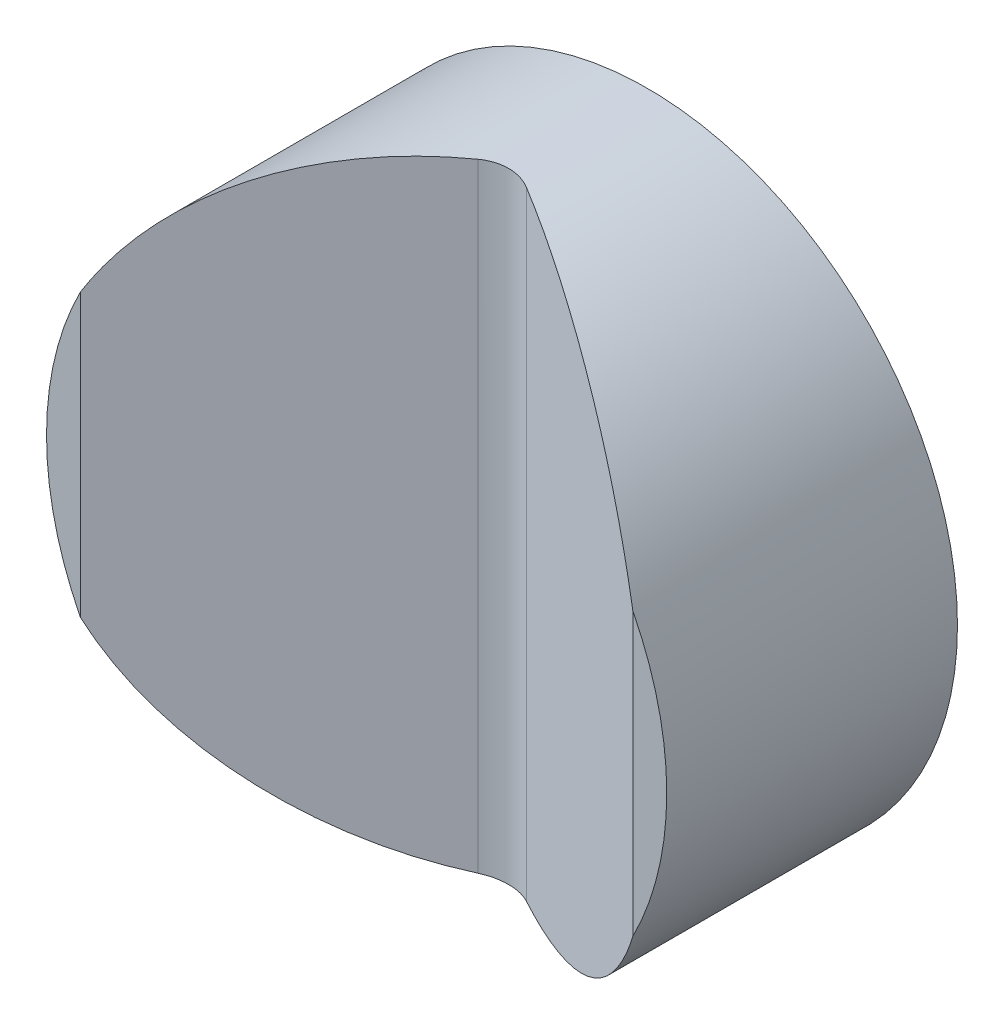
SolidWorks part; units mm, degrees
material "1.0553 (S355J0)"
ref_plane "XY Plane" through (0, 0, 0) normal (0, 0, 1) x (1, 0, 0)
ref_plane "XZ Plane" through (0, 0, 0) normal (0, 1, 0) x (1, 0, 0)
ref_plane "YZ Plane" through (0, 0, 0) normal (1, 0, 0) x (0, 0, -1)
sketch "Sketch1" plane through (0, 0, 0) normal (1, 0, 0) x (0, 0, -1)
  line L0 (8, 0) -> (8, 6)
  line L1 (8, 6) -> (0, 6)
  line L2 (0, 6) -> (0, 32)
  line L3 (0, 32) -> (-30, 32)
  line L4 (-30, 32) -> (-30, 0)
  line L5 (-30, 0) -> (8, 0)
  line L6 (8, 0) -> (13.5991, 0) construction
  dimension "D1" = 64
  dimension "D2" = 12
  dimension "D3" = 8
  dimension "D4" = 30
  dimension "D5" = 38
revolve "Revolve1" add sketch "Sketch1" angle 360 about L6
sketch "Sketch2" plane through (0, 0, 0) normal (0, 1, 0) x (1, 0, 0)
  line L0 (-28.5, -30) -> (-2.5, -14.9889)
  line L1 (-32, -30) -> (32, -30) construction
  line L2 (2.5, -14.9889) -> (28.5, -30)
  line L3 (-28.5, -30) -> (28.5, -30)
  line L4 (0, 0) -> (0, -30) construction
  arc A0 (-2.5, -14.9889) -> (2.5, -14.9889) centre (0, -19.319) cw
  point P8 (0, -13.9433)
  point P11 (0, -13.5455)
  point P12 (0, -14.319)
  dimension "D1" = 5
  dimension "D2" = 57
  dimension "D3" = 15.681
  dimension "D4" = 120
extrude "Cut-Extrude1" cut sketch "Sketch2" against normal mid plane 70 contours L3 L2 A0 L0
